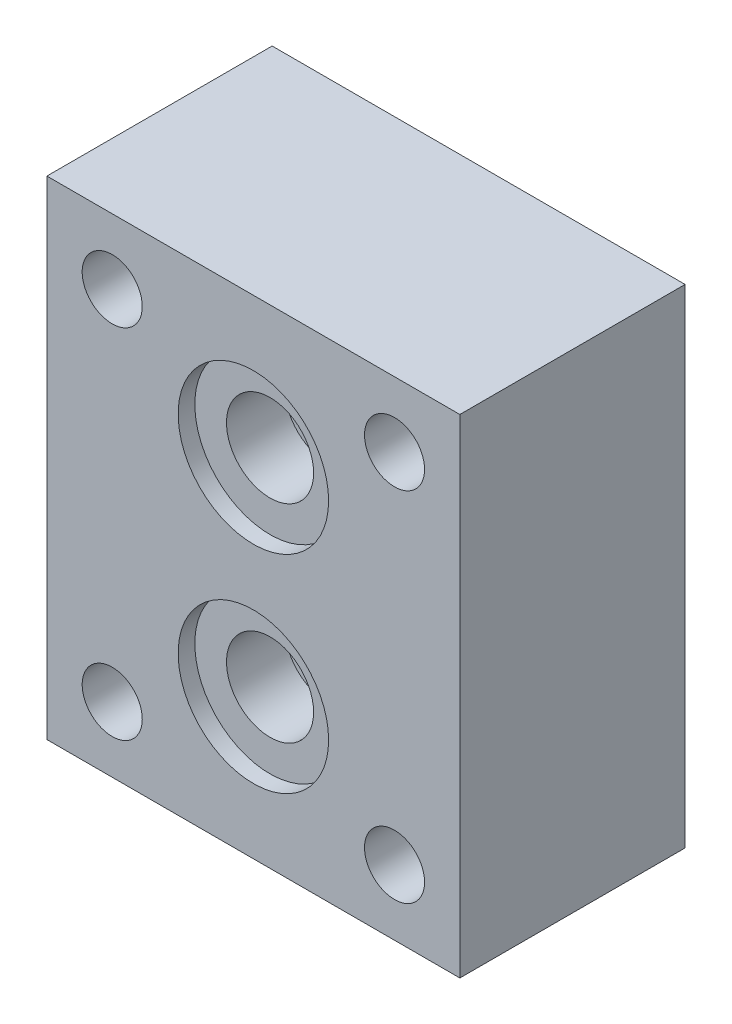
SolidWorks part; units mm, degrees
ref_plane "Front Plane" through (0, 0, 0) normal (1, 0, 0) x (0, 1, 0)
ref_plane "Top Plane" through (0, 0, 0) normal (0, 0, 1) x (0, 1, 0)
ref_plane "Right Plane" through (0, 0, 0) normal (0, 1, 0) x (-1, 0, 0)
sketch "Sketch1" plane through (0, 0, 0) normal (0, 0, 1) x (0, 1, 0)
  line L1 (-41.275, -34.925) -> (41.275, -34.925)
  line L2 (-41.275, -34.925) -> (-41.275, 34.925)
  line L3 (-41.275, 34.925) -> (41.275, 34.925)
  line L4 (41.275, -34.925) -> (41.275, 34.925)
  line L5 (-41.275, -34.925) -> (41.275, 34.925) construction
  line L6 (-41.275, 34.925) -> (41.275, -34.925) construction
  point P0 (0, 0)
  dimension "D1" = 41.275
  dimension "D2" = 34.925
extrude "Boss-Extrude1" add sketch "Sketch1" along normal mid plane 38.1
sketch "Sketch2" plane through (0, 0, 0) normal (0, 0, 1) x (0, 1, 0)
  circle A0 centre (-30.226, -23.876) radius 5.08
  circle A1 centre (30.226, -23.876) radius 5.08
  circle A2 centre (-30.226, 23.876) radius 5.08
  circle A3 centre (30.226, 23.876) radius 5.08
  dimension "D1" = 10.16
  dimension "D2" = 10.16
  dimension "D3" = 10.16
  dimension "D4" = 10.16
  dimension "D5" = 60.452
  dimension "D6" = 60.452
  dimension "D7" = 47.752
  dimension "D8" = 47.752
extrude "Cut-Extrude2" cut sketch "Sketch2" against normal through all from offset 19.05
sketch "Sketch3" plane through (0, 0, 0) normal (0, 0, 1) x (0, 1, 0)
  circle A0 centre (-17.526, 0) radius 7.366
  circle A1 centre (17.526, 0) radius 7.366
  dimension "D1" = 14.732
  dimension "D2" = 14.732
  dimension "D3" = 35.052
extrude "Cut-Extrude4" cut sketch "Sketch3" against normal blind 12.7 from offset 19.05
sketch "Sketch4" plane through (0, 0, 0) normal (0, 0, 1) x (0, 1, 0)
  circle A0 centre (-17.526, 0) radius 12.7254
  circle A1 centre (17.526, 0) radius 12.7254
  dimension "D1" = 25.4508
  dimension "D2" = 25.4508
  dimension "D3" = 35.052
extrude "Cut-Extrude6" cut sketch "Sketch4" against normal blind 2.8194 from offset 19.05
